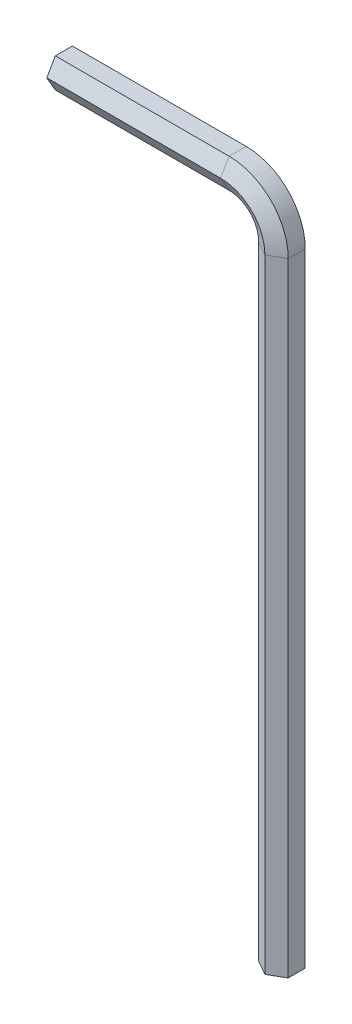
SolidWorks part; units mm, degrees
ref_plane "Front Plane" through (0, 0, 0) normal (0, 0, 1) x (1, 0, 0)
ref_plane "Top Plane" through (0, 0, 0) normal (0, 1, 0) x (1, 0, 0)
ref_plane "Right Plane" through (0, 0, 0) normal (1, 0, 0) x (0, 0, -1)
sketch "Sketch1" plane through (0, 0, 0) normal (0, 1, 0) x (1, 0, 0)
  line L1 (0, 1.4434) -> (-1.25, 0.7217)
  line L2 (-1.25, 0.7217) -> (-1.25, -0.7217)
  line L3 (-1.25, -0.7217) -> (0, -1.4434)
  line L4 (0, -1.4434) -> (1.25, -0.7217)
  line L5 (1.25, -0.7217) -> (1.25, 0.7217)
  line L6 (1.25, 0.7217) -> (0, 1.4434)
  circle A0 centre (0, 0) radius 1.25 construction
  dimension "D1" = 2.5
sketch "Sketch2" plane through (0, 0, 0) normal (0, 0, 1) x (1, 0, 0)
  line L0 (0, 0) -> (0, 52.7)
  line L1 (-3.75, 56.45) -> (-18.45, 56.45)
  arc A0 (0, 52.7) -> (-3.75, 56.45) centre (-3.75, 52.7) ccw
  point P6 (0, 56.45)
  dimension "D3" = 3.75
  dimension "D1" = 56.45
  dimension "D2" = 18.45
sweep "Sweep1" add profiles "Sketch1" path "Sketch2"
